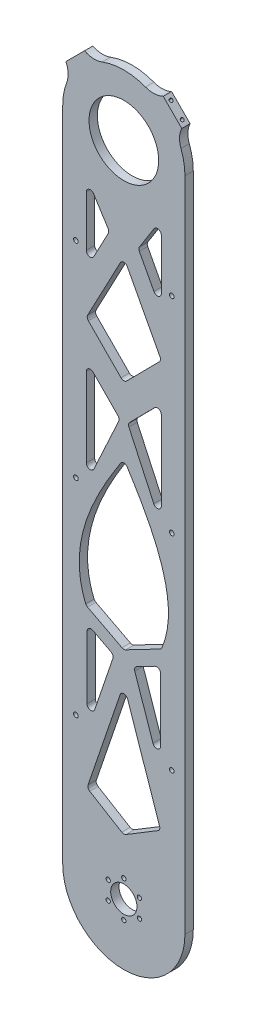
SolidWorks part; units mm, degrees
material "1060 Alloy"
ref_plane "Front Plane" through (0, 0, 0) normal (0, 0, 1) x (1, 0, 0)
ref_plane "Top Plane" through (0, 0, 0) normal (0, 1, 0) x (1, 0, 0)
ref_plane "Right Plane" through (0, 0, 0) normal (1, 0, 0) x (0, 0, -1)
sketch "Sketch2" plane through (0, 0, 0) normal (0, 0, 1) x (1, 0, 0)
  line L0 (0, 0) -> (0, 500) construction
  line L1 (-46.5, 0) -> (-46.5, 500)
  line L2 (46.5, 0) -> (46.5, 500)
  arc A0 (-46.5, 0) -> (46.5, 0) centre (0, 0) ccw
  arc A1 (46.5, 500) -> (-46.5, 500) centre (0, 500) ccw
  circle A2 centre (0, 500) radius 37.25 construction
  circle A3 centre (0, 0) radius 10
  circle A4 centre (0, 13.75) radius 1.65
  circle A5 centre (0, 0) radius 13.75 construction
  circle A6 centre (11.9078, 6.875) radius 1.65
  circle A7 centre (11.9078, -6.875) radius 1.65
  circle A8 centre (0, -13.75) radius 1.65
  circle A9 centre (-11.9078, -6.875) radius 1.65
  circle A10 centre (-11.9078, 6.875) radius 1.65
  point P3 (0, 250)
  point P27 (0, 0)
  dimension "D2" = 74.5
  dimension "D4" = 20
  dimension "D5" = 3.3
  dimension "D6" = 27.5
  dimension "D3" = 46.5
  dimension "D1" = 500
  dimension "D7" = 6
extrude "Boss-Extrude1" add sketch "Sketch2" along normal blind 6.35
sketch "Sketch4" plane through (0, 0, 6.35) normal (0, 0, 1) x (1, 0, 0)
  line L0 (0, 500) -> (0, 999.1647) construction
  line L29 (46.5, 500) -> (-46.5, 500) construction
  line L31 (28.0053, 59.376) -> (0, 42.4117)
  line L32 (0, 141.6934) -> (28.0053, 59.376)
  line L33 (-28.0053, 59.376) -> (0, 141.6934)
  line L34 (0, 42.4117) -> (-28.0053, 59.376)
  line L35 (-7.5, 156.9059) -> (-28.0053, 96.6336)
  line L36 (-28.0053, 167.5829) -> (-7.5, 156.9059)
  line L37 (-28.0053, 96.6336) -> (-28.0053, 167.5829)
  line L38 (28.0053, 167.5829) -> (7.5, 156.9059)
  line L39 (28.0053, 96.6336) -> (28.0053, 167.5829)
  line L40 (7.5, 156.9059) -> (28.0053, 96.6336)
  line L41 (0, 164.2751) -> (28.5505, 179.1412)
  line L42 (0, 164.2751) -> (-28.5505, 179.1412)
  line L43 (28.5505, 259.5868) -> (3, 314.9383)
  line L44 (28.5505, 340.7931) -> (28.5505, 259.5868)
  line L45 (3, 314.9383) -> (28.5505, 340.7931)
  line L46 (-3, 314.9383) -> (-28.5505, 340.7931)
  line L47 (-28.5505, 259.5868) -> (-3, 314.9383)
  line L48 (-28.5505, 340.7931) -> (-28.5505, 259.5868)
  line L49 (0, 423.1428) -> (-28.5505, 369.2462)
  line L50 (-28.5505, 369.2462) -> (0, 340.3557)
  line L51 (0, 340.3557) -> (28.5505, 369.2462)
  line L52 (0, 423.1428) -> (28.5505, 369.2462)
  line L53 (-28.5505, 462.0952) -> (-28.5505, 401.2902)
  line L54 (-11, 434.4215) -> (-28.5505, 462.0952)
  line L55 (-28.5505, 401.2902) -> (-11, 434.4215)
  line L56 (28.5505, 401.2902) -> (11, 434.4215)
  line L57 (28.5505, 462.0952) -> (28.5505, 401.2902)
  line L58 (11, 434.4215) -> (28.5505, 462.0952)
  arc A0 (46.5, 500) -> (-46.5, 500) centre (0, 500) ccw construction
  arc A1 (46.5, 500) -> (-46.5, 500) centre (0, 500) ccw construction
  spline S2 degree 3 poles (28.5505, 179.1412) (45.3203, 216.9857) (19.4301, 259.7903) (0, 290.0258) knots 0 0 0 0 1 1 1 1
  spline S3 degree 3 poles (-28.5505, 179.1412) (-45.3203, 216.9857) (-19.4301, 259.7903) (0, 290.0258) knots 0 0 0 0 1 1 1 1
extrude "Cut-Extrude1" cut sketch "Sketch4" against normal blind 10
fillet "Fillet3" radius 3 30 edges at (-11, 434.4215, 3.175) (-28.5505, 401.2902, 3.175) (28.5505, 401.2902, 3.175) (11, 434.4215, 3.175) (28.5505, 462.0952, 3.175) (-28.5505, 462.0952, 3.175) (0, 423.1428, 3.175) (-28.5505, 369.2462, 3.175) (28.5505, 369.2462, 3.175) (0, 340.3557, 3.175) (28.5505, 340.7931, 3.175) (-28.5505, 340.7931, 3.175) (-3, 314.9383, 3.175) (3, 314.9383, 3.175) (28.5505, 259.5868, 3.175) (-28.5505, 259.5868, 3.175) (28.5505, 179.1412, 3.175) (0, 290.0258, 3.175) (-28.5505, 179.1412, 3.175) (0, 164.2751, 3.175) (-28.0053, 96.6336, 3.175) (28.0053, 96.6336, 3.175) (7.5, 156.9059, 3.175) (-28.0053, 167.5829, 3.175) (28.0053, 167.5829, 3.175) (0, 141.6934, 3.175) (28.0053, 59.376, 3.175) (-28.0053, 59.376, 3.175) (0, 42.4117, 3.175) (-7.5, 156.9059, 3.175)
sketch "Sketch5" plane through (0, 0, 6.35) normal (0, 0, 1) x (1, 0, 0)
  line L0 (0, -46.5) -> (108.8395, -46.5) construction
  line L1 (46.5, 100) -> (-46.5, 100) construction
  line L2 (46.5, 0) -> (46.5, 500) construction
  line L3 (-46.5, 500) -> (-46.5, 0) construction
  line L4 (-46.5, 106.35) -> (46.5, 106.35) construction
  line L5 (36.5, 106.35) -> (36.5, 100) construction
  line L6 (0, 106.35) -> (0, 100) construction
  line L7 (-46.5, 256.35) -> (46.5, 256.35) construction
  line L8 (-46.5, 181.35) -> (46.5, 181.35) construction
  line L9 (-46.5, 337.7) -> (46.5, 337.7) construction
  arc A1 (-46.5, 0) -> (46.5, 0) centre (0, 0) ccw construction
  circle A2 centre (36.5, 103.175) radius 1.75
  circle A3 centre (-36.5, 103.175) radius 1.75
  circle A4 centre (36.5, 259.525) radius 1.75
  circle A5 centre (-36.5, 259.525) radius 1.75
  circle A6 centre (36.5, 415.875) radius 1.75
  circle A7 centre (-36.5, 415.875) radius 1.75
  point P18 (36.5, 103.175)
  dimension "D2" = 3.5
  dimension "D1" = 146.5
  dimension "D3" = 10
  dimension "D4" = 6.35
  dimension "D5" = 150
  dimension "D6" = 81.35
  dimension "D7" = 81.35
extrude "Cut-Extrude2" cut sketch "Sketch5" against normal through all
sketch "Sketch6" plane through (0, 0, 6.35) normal (0, 0, 1) x (1, 0, 0)
  circle A0 centre (0, 500) radius 26.5
  arc A1 (46.5, 500) -> (-46.5, 500) centre (0, 500) ccw construction
  arc A2 (46.5, 500) -> (-46.5, 500) centre (0, 500) ccw construction
  dimension "D1" = 20
extrude "Cut-Extrude3" cut sketch "Sketch6" against normal blind 10
sketch "Sketch7" plane through (0, 0, 6.35) normal (0, 0, 1) x (1, 0, 0)
  line L1 (40.0163, 523.6842) -> (44.1104, 529.9682) construction
  line L2 (23.6842, 540.0163) -> (29.9682, 544.1104) construction
  line L3 (44.1104, 529.9682) -> (29.9682, 544.1104)
  line L4 (0, 500) -> (37.0393, 537.0393) construction
  line L5 (0, 500) -> (0, 546.5) construction
  arc A0 (46.5, 500) -> (-46.5, 500) centre (0, 500) ccw construction
  arc A1 (29.9682, 544.1104) -> (16.4747, 543.4837) centre (22.4977, 559.381) cw
  arc A2 (44.1104, 529.9682) -> (43.4837, 516.4747) centre (59.381, 522.4977) ccw
  arc A3 (16.4747, 543.4837) -> (43.4837, 516.4747) centre (0, 500) cw
  dimension "D3" = 17
  dimension "D5" = 17
  dimension "D1" = 20
  dimension "D2" = 7.5
  dimension "D4" = 8
  dimension "D6" = 8
  dimension "D7" = 45
extrude "Boss-Extrude2" add sketch "Sketch7" against normal up to surface (6.35 mm away) up to face at (26.5, 500, 0)
sketch "Sketch8" plane through (287.0393, 287.0393, 0) normal (0.7071, 0.7071, 0) x (0, 0, -1)
  line L0 (0, 363.5534) -> (-6.35, 363.5534) construction
  line L1 (0, 343.5534) -> (-6.35, 343.5534) construction
  line L2 (-6.35, 343.5534) -> (-6.35, 363.5534) construction
  point P0 (-3.175, 359.5534)
  point P1 (-3.175, 347.5534)
  dimension "D1" = 4
  dimension "D2" = 4
  dimension "D3" = 3.175
hole_wizard "Tap Drill for M3x0.5 Tap1" positions "Sketch8" profile "Sketch9" hole size "M3x0.5" standard "ANSI Metric"
sketch "Sketch9" plane through (32.7967, 541.282, 3.175) normal (0, 0, 1) x (-0.7071, 0.7071, 0)
  line L0 (0, 0) -> (0, 5.7511)
  line L1 (0, 5.7511) -> (1.25, 5)
  line L2 (1.25, 5) -> (1.25, 0)
  line L5 (1.25, 0) -> (0, 0)
  line L10 (0, 5.7511) -> (-1.25, 5) construction
  line L11 (0, -6.35) -> (0, 107.95) construction
  dimension "Hole Dia." = 2.5
  dimension "Hole Depth" = 5
  dimension "Drill Angle" = 118
pattern_circular "CirPattern2" count 2 every 90 about axis through (0, 500, 0) along (0, 0, 1) of "Boss-Extrude2", "Tap Drill for M3x0.5 Tap1"
equation "\"L1L\"=500"
equation "\"L1Thick\"=6.35"
equation "\"D1@Sketch2\"=\"L1L\""
equation "\"Harm-Drive-Outer\"=74.5"
equation "\"D2@Sketch2\"=\"Harm-Drive-Outer\""
equation "\"D1@Boss-Extrude1\"=\"L1Thick\""
